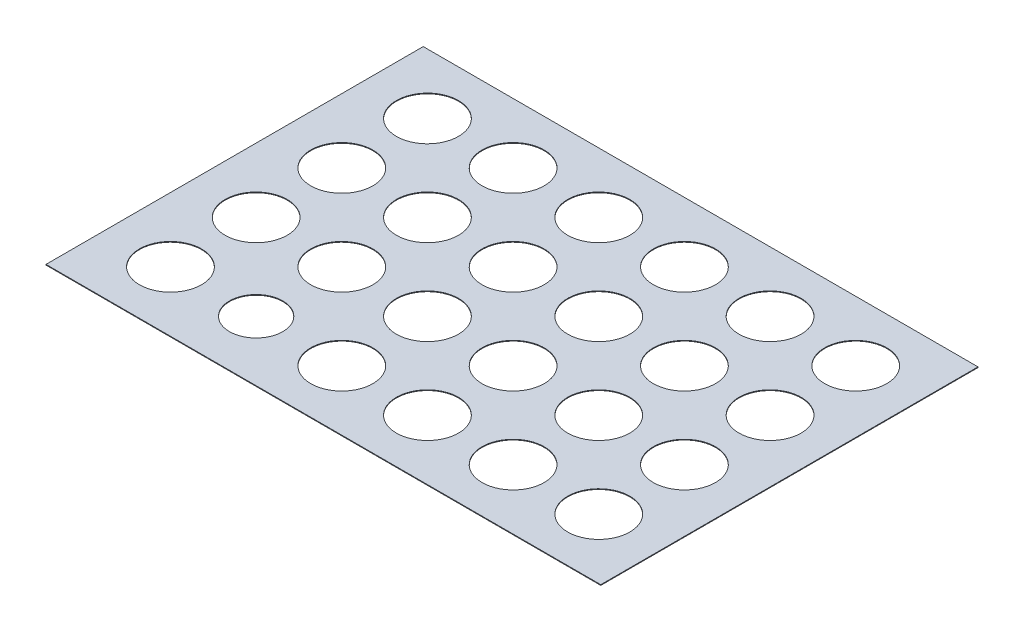
SolidWorks part; units mm, degrees
ref_plane "Front Plane" through (0, 0, 0) normal (0, 0, 1) x (1, 0, 0)
ref_plane "Top Plane" through (0, 0, 0) normal (0, 1, 0) x (1, 0, 0)
ref_plane "Right Plane" through (0, 0, 0) normal (1, 0, 0) x (0, 0, -1)
sketch "Sketch1" plane through (0, 0, 0) normal (0, 1, 0) x (1, 0, 0)
  line L1 (0, 0) -> (125, 0)
  line L2 (0, 0) -> (0, 85)
  line L3 (0, 85) -> (125, 85)
  line L4 (125, 0) -> (125, 85)
  dimension "D1" = 125
  dimension "D2" = 85
extrude "Boss-Extrude1" add sketch "Sketch1" along normal blind 0.15
sketch "Sketch2" plane through (0, 0.15, 0) normal (0, 1, 0) x (1, 0, 0)
  line L0 (0, 85) -> (0, 0) construction
  line L1 (0, 0) -> (125, 0) construction
  circle A0 centre (14.5, 13.55) radius 7
  circle A1 centre (14.5, 32.85) radius 7
  circle A2 centre (14.5, 52.15) radius 7
  circle A3 centre (14.5, 71.45) radius 7
  circle A4 centre (33.8, 71.45) radius 7
  circle A5 centre (53.1, 71.45) radius 7
  circle A6 centre (72.4, 71.45) radius 7
  circle A7 centre (91.7, 71.45) radius 7
  circle A8 centre (111, 71.45) radius 7
  circle A9 centre (33.8, 52.15) radius 7
  circle A10 centre (33.8, 32.85) radius 7
  circle A11 centre (53.1, 52.15) radius 7
  circle A12 centre (53.1, 32.85) radius 7
  circle A13 centre (72.4, 52.15) radius 7
  circle A14 centre (91.7, 52.15) radius 7
  circle A15 centre (111, 52.15) radius 7
  circle A16 centre (72.4, 32.85) radius 7
  circle A17 centre (91.7, 32.85) radius 7
  circle A18 centre (111, 32.85) radius 7
  circle A19 centre (33.8, 13.55) radius 6.0056
  circle A20 centre (53.1, 13.55) radius 7
  circle A21 centre (72.4, 13.55) radius 7
  circle A22 centre (91.7, 13.55) radius 7
  circle A23 centre (111, 13.55) radius 7
  dimension "D2" = 14
  dimension "D6" = 14
  dimension "D7" = 14
  dimension "D8" = 14
  dimension "D14" = 14
  dimension "D15" = 14
  dimension "D16" = 14
  dimension "D17" = 14
  dimension "D18" = 14
  dimension "D19" = 14
  dimension "D20" = 14
  dimension "D21" = 14
  dimension "D22" = 14
  dimension "D23" = 14
  dimension "D24" = 14
  dimension "D25" = 14
  dimension "D26" = 14
  dimension "D27" = 14
  dimension "D28" = 14
  dimension "D29" = 14
  dimension "D30" = 14
  dimension "D31" = 14
  dimension "D32" = 14
  dimension "D1" = 14.5
  dimension "D3" = 13.55
  dimension "D4" = 19.3
  dimension "D5" = 19.3
  dimension "19.3" = 19.3
  dimension "D9" = 19.3
  dimension "D10" = 19.3
  dimension "D11" = 19.3
  dimension "D12" = 19.3
  dimension "D13" = 19.3
extrude "Cut-Extrude1" cut sketch "Sketch2" against normal blind 0.15
